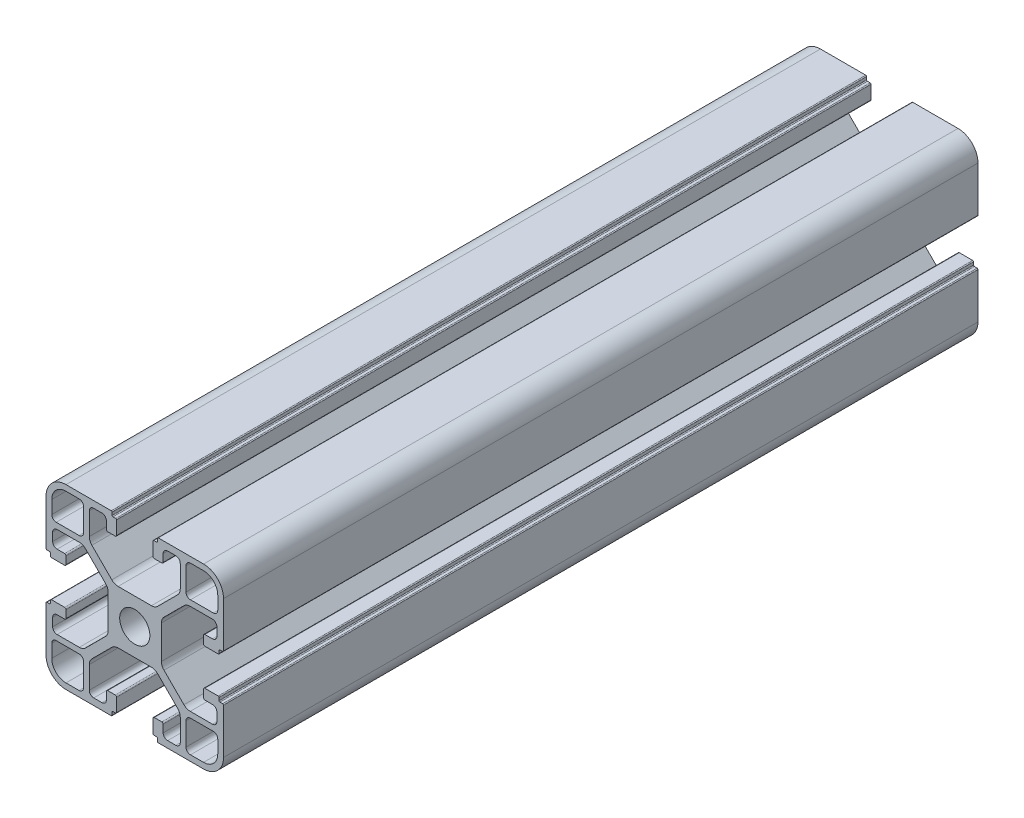
SolidWorks part; units mm, degrees
material "6063-T5"
ref_plane "Front Plane" through (0, 0, 0) normal (0, 0, 1) x (1, 0, 0)
ref_plane "Top Plane" through (0, 0, 0) normal (0, 1, 0) x (1, 0, 0)
ref_plane "Right Plane" through (0, 0, 0) normal (1, 0, 0) x (0, 0, -1)
sketch "Sketch2" plane through (0, 0, 0) normal (0, 0, 1) x (1, 0, 0)
  line L0 (4.5, 0) -> (14.7, 0)
  line L1 (40, 4.5) -> (40, 14.7)
  line L2 (35.5, 40) -> (25.3, 40)
  line L3 (0, 35.5) -> (0, 25.3)
  line L4 (15.9, 1.2) -> (15.9, 4.2)
  line L5 (24.1, 1.2) -> (24.1, 4.2)
  line L6 (38.8, 24.1) -> (35.8, 24.1)
  line L7 (35.5, 24.4) -> (35.5, 26.1)
  line L8 (14, 23.7574) -> (14, 16.2426)
  line L9 (16.2426, 14) -> (23.7574, 14)
  line L10 (26, 16.2426) -> (26, 23.7574)
  line L11 (13.4142, 14.8284) -> (8.9216, 10.3358)
  line L12 (23.7574, 26) -> (16.2426, 26)
  line L13 (4.5, 24.4) -> (4.5, 26.1)
  line L14 (1.2, 24.1) -> (4.2, 24.1)
  line L15 (15.9, 38.8) -> (15.9, 35.8)
  line L16 (14.8284, 26.5858) -> (10.3358, 31.0784)
  line L17 (13.4142, 25.1716) -> (8.9216, 29.6642)
  line L18 (14.8284, 13.4142) -> (10.3358, 8.9216)
  line L19 (25.1716, 13.4142) -> (29.6642, 8.9216)
  line L20 (26.5858, 14.8284) -> (31.0784, 10.3358)
  line L21 (26.5858, 25.1716) -> (31.0784, 29.6642)
  line L22 (25.1716, 26.5858) -> (29.6642, 31.0784)
  line L23 (24.1, 38.8) -> (24.1, 35.8)
  line L24 (14.7, 40) -> (4.5, 40)
  line L25 (25.3, 0) -> (35.5, 0)
  line L26 (38.8, 15.9) -> (35.8, 15.9)
  line L27 (40, 25.3) -> (40, 35.5)
  line L28 (1.2, 15.9) -> (4.2, 15.9)
  line L29 (0, 14.7) -> (0, 4.5)
  line L30 (4.5, 15.6) -> (4.5, 13.9)
  line L31 (35.5, 15.6) -> (35.5, 13.9)
  line L32 (15.6, 35.5) -> (13.9, 35.5)
  line L33 (24.4, 35.5) -> (26.1, 35.5)
  line L34 (15.6, 4.5) -> (13.9, 4.5)
  line L35 (24.4, 4.5) -> (26.1, 4.5)
  line L36 (12.6, 38.5) -> (10.75, 38.5)
  line L37 (1.5, 12.6) -> (1.5, 10.75)
  line L38 (27.4, 1.5) -> (29.25, 1.5)
  line L39 (38.5, 27.4) -> (38.5, 29.25)
  line L40 (38.5, 10.75) -> (38.5, 12.6)
  line L41 (29.25, 38.5) -> (27.4, 38.5)
  line L42 (1.5, 29.25) -> (1.5, 27.4)
  line L43 (10.75, 1.5) -> (12.6, 1.5)
  line L44 (35.8, 26.4) -> (37.5, 26.4)
  line L45 (35.8, 13.6) -> (37.5, 13.6)
  line L46 (4.2, 26.4) -> (2.5, 26.4)
  line L47 (13.6, 35.8) -> (13.6, 37.5)
  line L48 (26.4, 35.8) -> (26.4, 37.5)
  line L49 (4.2, 13.6) -> (2.5, 13.6)
  line L50 (13.6, 4.2) -> (13.6, 2.5)
  line L51 (26.4, 4.2) -> (26.4, 2.5)
  line L52 (9.75, 7.5074) -> (9.75, 2.5)
  line L53 (30.25, 7.5074) -> (30.25, 2.5)
  line L54 (9.75, 37.5) -> (9.75, 32.4926)
  line L55 (30.25, 37.5) -> (30.25, 32.4926)
  line L56 (32.4926, 30.25) -> (37.5, 30.25)
  line L57 (37.5, 9.75) -> (32.4926, 9.75)
  line L58 (2.5, 30.25) -> (7.5074, 30.25)
  line L59 (2.5, 9.75) -> (7.5074, 9.75)
  line L60 (31.55, 37.7) -> (31.55, 32.55)
  line L61 (32.55, 31.55) -> (37.7, 31.55)
  line L62 (1.3, 35.5) -> (1.3, 32.55)
  line L63 (4.5, 38.7) -> (7.45, 38.7)
  line L64 (32.55, 38.7) -> (35.5, 38.7)
  line L65 (38.7, 35.5) -> (38.7, 32.55)
  line L66 (8.45, 37.7) -> (8.45, 32.55)
  line L67 (2.3, 31.55) -> (7.45, 31.55)
  line L68 (1.3, 7.45) -> (1.3, 4.5)
  line L69 (2.3, 8.45) -> (7.45, 8.45)
  line L70 (8.45, 7.45) -> (8.45, 2.3)
  line L71 (4.5, 1.3) -> (7.45, 1.3)
  line L72 (31.55, 7.45) -> (31.55, 2.3)
  line L73 (32.55, 8.45) -> (37.7, 8.45)
  line L74 (38.7, 7.45) -> (38.7, 4.5)
  line L75 (32.55, 1.3) -> (35.5, 1.3)
  line L77 (14.9, 39.8) -> (14.9, 39.2)
  line L78 (15.1, 39) -> (15.7, 39)
  line L79 (25.1, 39.8) -> (25.1, 39.2)
  line L80 (24.9, 39) -> (24.3, 39)
  line L81 (25.1, 0.2) -> (25.1, 0.8)
  line L82 (24.9, 1) -> (24.3, 1)
  line L83 (14.9, 0.2) -> (14.9, 0.8)
  line L84 (15.1, 1) -> (15.7, 1)
  line L85 (0.2, 25.1) -> (0.8, 25.1)
  line L86 (1, 24.9) -> (1, 24.3)
  line L87 (0.2, 14.9) -> (0.8, 14.9)
  line L88 (1, 15.1) -> (1, 15.7)
  line L89 (39.8, 25.1) -> (39.2, 25.1)
  line L90 (39, 24.9) -> (39, 24.3)
  line L91 (39, 15.7) -> (39, 15.1)
  line L92 (39.2, 14.9) -> (39.8, 14.9)
  circle A0 centre (20, 20) radius 3.4
  arc A1 (1.3, 35.5) -> (4.5, 38.7) centre (4.5, 35.5) cw
  arc A2 (1.3, 4.5) -> (4.5, 1.3) centre (4.5, 4.5) ccw
  arc A3 (38.7, 4.5) -> (35.5, 1.3) centre (35.5, 4.5) cw
  arc A4 (35.5, 38.7) -> (38.7, 35.5) centre (35.5, 35.5) cw
  arc A5 (40, 35.5) -> (35.5, 40) centre (35.5, 35.5) ccw
  arc A6 (35.5, 0) -> (40, 4.5) centre (35.5, 4.5) ccw
  arc A7 (4.5, 0) -> (0, 4.5) centre (4.5, 4.5) cw
  arc A8 (4.5, 40) -> (0, 35.5) centre (4.5, 35.5) ccw
  arc A9 (13.4142, 14.8284) -> (14, 16.2426) centre (12, 16.2426) ccw
  arc A10 (7.5074, 9.75) -> (8.9216, 10.3358) centre (7.5074, 11.75) ccw
  arc A11 (9.75, 7.5074) -> (10.3358, 8.9216) centre (11.75, 7.5074) cw
  arc A12 (30.25, 7.5074) -> (29.6642, 8.9216) centre (28.25, 7.5074) ccw
  arc A13 (14.8284, 13.4142) -> (16.2426, 14) centre (16.2426, 12) cw
  arc A14 (25.1716, 13.4142) -> (23.7574, 14) centre (23.7574, 12) ccw
  arc A15 (32.4926, 9.75) -> (31.0784, 10.3358) centre (32.4926, 11.75) cw
  arc A16 (26.5858, 14.8284) -> (26, 16.2426) centre (28, 16.2426) cw
  arc A17 (32.4926, 30.25) -> (31.0784, 29.6642) centre (32.4926, 28.25) ccw
  arc A18 (26.5858, 25.1716) -> (26, 23.7574) centre (28, 23.7574) ccw
  arc A19 (13.4142, 25.1716) -> (14, 23.7574) centre (12, 23.7574) cw
  arc A20 (7.5074, 30.25) -> (8.9216, 29.6642) centre (7.5074, 28.25) cw
  arc A21 (9.75, 32.4926) -> (10.3358, 31.0784) centre (11.75, 32.4926) ccw
  arc A22 (30.25, 32.4926) -> (29.6642, 31.0784) centre (28.25, 32.4926) cw
  arc A23 (25.1716, 26.5858) -> (23.7574, 26) centre (23.7574, 28) cw
  arc A24 (14.8284, 26.5858) -> (16.2426, 26) centre (16.2426, 28) ccw
  arc A25 (37.7, 8.45) -> (38.7, 7.45) centre (37.7, 7.45) cw
  arc A26 (31.55, 2.3) -> (32.55, 1.3) centre (32.55, 2.3) ccw
  arc A27 (31.55, 7.45) -> (32.55, 8.45) centre (32.55, 7.45) cw
  arc A28 (8.45, 2.3) -> (7.45, 1.3) centre (7.45, 2.3) cw
  arc A29 (1.3, 7.45) -> (2.3, 8.45) centre (2.3, 7.45) cw
  arc A30 (7.45, 8.45) -> (8.45, 7.45) centre (7.45, 7.45) cw
  arc A31 (38.7, 32.55) -> (37.7, 31.55) centre (37.7, 32.55) cw
  arc A32 (31.55, 32.55) -> (32.55, 31.55) centre (32.55, 32.55) ccw
  arc A33 (31.55, 37.7) -> (32.55, 38.7) centre (32.55, 37.7) cw
  arc A34 (7.45, 38.7) -> (8.45, 37.7) centre (7.45, 37.7) cw
  arc A35 (8.45, 32.55) -> (7.45, 31.55) centre (7.45, 32.55) cw
  arc A36 (1.3, 32.55) -> (2.3, 31.55) centre (2.3, 32.55) ccw
  arc A37 (30.25, 2.5) -> (29.25, 1.5) centre (29.25, 2.5) cw
  arc A38 (26.4, 2.5) -> (27.4, 1.5) centre (27.4, 2.5) ccw
  arc A39 (13.6, 2.5) -> (12.6, 1.5) centre (12.6, 2.5) cw
  arc A40 (9.75, 2.5) -> (10.75, 1.5) centre (10.75, 2.5) ccw
  arc A41 (26.4, 37.5) -> (27.4, 38.5) centre (27.4, 37.5) cw
  arc A42 (30.25, 37.5) -> (29.25, 38.5) centre (29.25, 37.5) ccw
  arc A43 (37.5, 26.4) -> (38.5, 27.4) centre (37.5, 27.4) ccw
  arc A44 (37.5, 30.25) -> (38.5, 29.25) centre (37.5, 29.25) cw
  arc A45 (37.5, 13.6) -> (38.5, 12.6) centre (37.5, 12.6) cw
  arc A46 (37.5, 9.75) -> (38.5, 10.75) centre (37.5, 10.75) ccw
  arc A47 (2.5, 9.75) -> (1.5, 10.75) centre (2.5, 10.75) cw
  arc A48 (2.5, 13.6) -> (1.5, 12.6) centre (2.5, 12.6) ccw
  arc A49 (2.5, 26.4) -> (1.5, 27.4) centre (2.5, 27.4) cw
  arc A50 (2.5, 30.25) -> (1.5, 29.25) centre (2.5, 29.25) ccw
  arc A51 (9.75, 37.5) -> (10.75, 38.5) centre (10.75, 37.5) cw
  arc A52 (13.6, 37.5) -> (12.6, 38.5) centre (12.6, 37.5) ccw
  arc A53 (26.1, 35.5) -> (26.4, 35.8) centre (26.1, 35.8) ccw
  arc A54 (24.1, 35.8) -> (24.4, 35.5) centre (24.4, 35.8) ccw
  arc A55 (15.9, 35.8) -> (15.6, 35.5) centre (15.6, 35.8) cw
  arc A56 (13.9, 35.5) -> (13.6, 35.8) centre (13.9, 35.8) cw
  arc A57 (13.9, 4.5) -> (13.6, 4.2) centre (13.9, 4.2) ccw
  arc A58 (15.9, 4.2) -> (15.6, 4.5) centre (15.6, 4.2) ccw
  arc A59 (24.1, 4.2) -> (24.4, 4.5) centre (24.4, 4.2) cw
  arc A60 (26.1, 4.5) -> (26.4, 4.2) centre (26.1, 4.2) cw
  arc A61 (35.5, 13.9) -> (35.8, 13.6) centre (35.8, 13.9) ccw
  arc A62 (35.8, 15.9) -> (35.5, 15.6) centre (35.8, 15.6) ccw
  arc A63 (35.8, 24.1) -> (35.5, 24.4) centre (35.8, 24.4) cw
  arc A64 (35.5, 26.1) -> (35.8, 26.4) centre (35.8, 26.1) cw
  arc A65 (4.5, 13.9) -> (4.2, 13.6) centre (4.2, 13.9) cw
  arc A66 (4.2, 15.9) -> (4.5, 15.6) centre (4.2, 15.6) cw
  arc A67 (4.2, 24.1) -> (4.5, 24.4) centre (4.2, 24.4) ccw
  arc A68 (4.5, 26.1) -> (4.2, 26.4) centre (4.2, 26.1) ccw
  arc A69 (25.3, 0) -> (25.1, 0.2) centre (25.3, 0.2) cw
  arc A70 (25.1, 0.8) -> (24.9, 1) centre (24.9, 0.8) ccw
  arc A71 (24.3, 1) -> (24.1, 1.2) centre (24.3, 1.2) cw
  arc A72 (14.7, 0) -> (14.9, 0.2) centre (14.7, 0.2) ccw
  arc A73 (14.9, 0.8) -> (15.1, 1) centre (15.1, 0.8) cw
  arc A74 (15.7, 1) -> (15.9, 1.2) centre (15.7, 1.2) ccw
  arc A75 (39.8, 14.9) -> (40, 14.7) centre (39.8, 14.7) cw
  arc A76 (39, 15.1) -> (39.2, 14.9) centre (39.2, 15.1) ccw
  arc A77 (38.8, 15.9) -> (39, 15.7) centre (38.8, 15.7) cw
  arc A78 (0, 25.3) -> (0.2, 25.1) centre (0.2, 25.3) ccw
  arc A79 (0.8, 25.1) -> (1, 24.9) centre (0.8, 24.9) cw
  arc A80 (1, 24.3) -> (1.2, 24.1) centre (1.2, 24.3) ccw
  arc A81 (0, 14.7) -> (0.2, 14.9) centre (0.2, 14.7) cw
  arc A82 (0.8, 14.9) -> (1, 15.1) centre (0.8, 15.1) ccw
  arc A83 (1, 15.7) -> (1.2, 15.9) centre (1.2, 15.7) cw
  arc A84 (39, 24.3) -> (38.8, 24.1) centre (38.8, 24.3) cw
  arc A85 (39.2, 25.1) -> (39, 24.9) centre (39.2, 24.9) ccw
  arc A86 (40, 25.3) -> (39.8, 25.1) centre (39.8, 25.3) cw
  arc A87 (24.3, 39) -> (24.1, 38.8) centre (24.3, 38.8) ccw
  arc A88 (25.1, 39.2) -> (24.9, 39) centre (24.9, 39.2) cw
  arc A89 (25.3, 40) -> (25.1, 39.8) centre (25.3, 39.8) ccw
  arc A90 (14.9, 39.2) -> (15.1, 39) centre (15.1, 39.2) ccw
  arc A91 (15.7, 39) -> (15.9, 38.8) centre (15.7, 38.8) cw
  arc A92 (14.7, 40) -> (14.9, 39.8) centre (14.7, 39.8) cw
  point P93 (0, 0)
extrude "Boss-Extrude1" add sketch "Sketch2" along normal blind 170
sketch "Sketch3" plane through (0, 0, 170) normal (0, 0, 1) x (1, 0, 0)
  line L76 (25.3, 0) -> (35.5, 0)
  line L77 (40, 4.5) -> (40, 14.7)
  line L78 (39.8, 14.9) -> (39.2, 14.9)
  line L79 (39, 15.1) -> (39, 15.7)
  line L80 (38.8, 15.9) -> (35.8, 15.9)
  line L81 (35.5, 15.6) -> (35.5, 13.9)
  line L82 (35.8, 13.6) -> (37.5, 13.6)
  line L83 (38.5, 12.6) -> (38.5, 10.75)
  line L84 (37.5, 9.75) -> (32.4926, 9.75)
  line L85 (31.0784, 10.3358) -> (26.5858, 14.8284)
  line L86 (26, 16.2426) -> (26, 23.7574)
  line L87 (26.5858, 25.1716) -> (31.0784, 29.6642)
  line L88 (32.4926, 30.25) -> (37.5, 30.25)
  line L89 (38.5, 29.25) -> (38.5, 27.4)
  line L90 (37.5, 26.4) -> (35.8, 26.4)
  line L91 (35.5, 26.1) -> (35.5, 24.4)
  line L92 (35.8, 24.1) -> (38.8, 24.1)
  line L93 (39, 24.3) -> (39, 24.9)
  line L94 (39.2, 25.1) -> (39.8, 25.1)
  line L95 (40, 25.3) -> (40, 35.5)
  line L96 (35.5, 40) -> (25.3, 40)
  line L97 (25.1, 39.8) -> (25.1, 39.2)
  line L98 (24.9, 39) -> (24.3, 39)
  line L99 (24.1, 38.8) -> (24.1, 35.8)
  line L100 (24.4, 35.5) -> (26.1, 35.5)
  line L101 (26.4, 35.8) -> (26.4, 37.5)
  line L102 (27.4, 38.5) -> (29.25, 38.5)
  line L103 (30.25, 37.5) -> (30.25, 32.4926)
  line L104 (29.6642, 31.0784) -> (25.1716, 26.5858)
  line L105 (23.7574, 26) -> (16.2426, 26)
  line L106 (14.8284, 26.5858) -> (10.3358, 31.0784)
  line L107 (9.75, 32.4926) -> (9.75, 37.5)
  line L108 (10.75, 38.5) -> (12.6, 38.5)
  line L109 (13.6, 37.5) -> (13.6, 35.8)
  line L110 (13.9, 35.5) -> (15.6, 35.5)
  line L111 (15.9, 35.8) -> (15.9, 38.8)
  line L112 (15.7, 39) -> (15.1, 39)
  line L113 (14.9, 39.2) -> (14.9, 39.8)
  line L114 (14.7, 40) -> (4.5, 40)
  line L115 (0, 35.5) -> (0, 25.3)
  line L116 (0.2, 25.1) -> (0.8, 25.1)
  line L117 (1, 24.9) -> (1, 24.3)
  line L118 (1.2, 24.1) -> (4.2, 24.1)
  line L119 (4.5, 24.4) -> (4.5, 26.1)
  line L120 (4.2, 26.4) -> (2.5, 26.4)
  line L121 (1.5, 27.4) -> (1.5, 29.25)
  line L122 (2.5, 30.25) -> (7.5074, 30.25)
  line L123 (8.9216, 29.6642) -> (13.4142, 25.1716)
  line L124 (14, 23.7574) -> (14, 16.2426)
  line L125 (13.4142, 14.8284) -> (8.9216, 10.3358)
  line L126 (7.5074, 9.75) -> (2.5, 9.75)
  line L127 (1.5, 10.75) -> (1.5, 12.6)
  line L128 (2.5, 13.6) -> (4.2, 13.6)
  line L129 (4.5, 13.9) -> (4.5, 15.6)
  line L130 (4.2, 15.9) -> (1.2, 15.9)
  line L131 (1, 15.7) -> (1, 15.1)
  line L132 (0.8, 14.9) -> (0.2, 14.9)
  line L133 (0, 14.7) -> (0, 4.5)
  line L134 (4.5, 0) -> (14.7, 0)
  line L135 (14.9, 0.2) -> (14.9, 0.8)
  line L136 (15.1, 1) -> (15.7, 1)
  line L137 (15.9, 1.2) -> (15.9, 4.2)
  line L138 (15.6, 4.5) -> (13.9, 4.5)
  line L139 (13.6, 4.2) -> (13.6, 2.5)
  line L140 (12.6, 1.5) -> (10.75, 1.5)
  line L141 (9.75, 2.5) -> (9.75, 7.5074)
  line L142 (10.3358, 8.9216) -> (14.8284, 13.4142)
  line L143 (16.2426, 14) -> (23.7574, 14)
  line L144 (25.1716, 13.4142) -> (29.6642, 8.9216)
  line L145 (30.25, 7.5074) -> (30.25, 2.5)
  line L146 (29.25, 1.5) -> (27.4, 1.5)
  line L147 (26.4, 2.5) -> (26.4, 4.2)
  line L148 (26.1, 4.5) -> (24.4, 4.5)
  line L149 (24.1, 4.2) -> (24.1, 1.2)
  line L150 (24.3, 1) -> (24.9, 1)
  line L151 (25.1, 0.8) -> (25.1, 0.2)
  line L152 (25.3, 0) -> (35.5, 0)
  line L153 (40, 4.5) -> (40, 14.7)
  line L154 (39.8, 14.9) -> (39.2, 14.9)
  line L155 (39, 15.1) -> (39, 15.7)
  line L156 (38.8, 15.9) -> (35.8, 15.9)
  line L157 (35.5, 15.6) -> (35.5, 13.9)
  line L158 (35.8, 13.6) -> (37.5, 13.6)
  line L159 (38.5, 12.6) -> (38.5, 10.75)
  line L160 (37.5, 9.75) -> (32.4926, 9.75)
  line L161 (31.0784, 10.3358) -> (26.5858, 14.8284)
  line L162 (26, 16.2426) -> (26, 23.7574)
  line L163 (26.5858, 25.1716) -> (31.0784, 29.6642)
  line L164 (32.4926, 30.25) -> (37.5, 30.25)
  line L165 (38.5, 29.25) -> (38.5, 27.4)
  line L166 (37.5, 26.4) -> (35.8, 26.4)
  line L167 (35.5, 26.1) -> (35.5, 24.4)
  line L168 (35.8, 24.1) -> (38.8, 24.1)
  line L169 (39, 24.3) -> (39, 24.9)
  line L170 (39.2, 25.1) -> (39.8, 25.1)
  line L171 (40, 25.3) -> (40, 35.5)
  line L172 (35.5, 40) -> (25.3, 40)
  line L173 (25.1, 39.8) -> (25.1, 39.2)
  line L174 (24.9, 39) -> (24.3, 39)
  line L175 (24.1, 38.8) -> (24.1, 35.8)
  line L176 (24.4, 35.5) -> (26.1, 35.5)
  line L177 (26.4, 35.8) -> (26.4, 37.5)
  line L178 (27.4, 38.5) -> (29.25, 38.5)
  line L179 (30.25, 37.5) -> (30.25, 32.4926)
  line L180 (29.6642, 31.0784) -> (25.1716, 26.5858)
  line L181 (23.7574, 26) -> (16.2426, 26)
  line L182 (14.8284, 26.5858) -> (10.3358, 31.0784)
  line L183 (9.75, 32.4926) -> (9.75, 37.5)
  line L184 (10.75, 38.5) -> (12.6, 38.5)
  line L185 (13.6, 37.5) -> (13.6, 35.8)
  line L186 (13.9, 35.5) -> (15.6, 35.5)
  line L187 (15.9, 35.8) -> (15.9, 38.8)
  line L188 (15.7, 39) -> (15.1, 39)
  line L189 (14.9, 39.2) -> (14.9, 39.8)
  line L190 (14.7, 40) -> (4.5, 40)
  line L191 (0, 35.5) -> (0, 25.3)
  line L192 (0.2, 25.1) -> (0.8, 25.1)
  line L193 (1, 24.9) -> (1, 24.3)
  line L194 (1.2, 24.1) -> (4.2, 24.1)
  line L195 (4.5, 24.4) -> (4.5, 26.1)
  line L196 (4.2, 26.4) -> (2.5, 26.4)
  line L197 (1.5, 27.4) -> (1.5, 29.25)
  line L198 (2.5, 30.25) -> (7.5074, 30.25)
  line L199 (8.9216, 29.6642) -> (13.4142, 25.1716)
  line L200 (14, 23.7574) -> (14, 16.2426)
  line L201 (13.4142, 14.8284) -> (8.9216, 10.3358)
  line L202 (7.5074, 9.75) -> (2.5, 9.75)
  line L203 (1.5, 10.75) -> (1.5, 12.6)
  line L204 (2.5, 13.6) -> (4.2, 13.6)
  line L205 (4.5, 13.9) -> (4.5, 15.6)
  line L206 (4.2, 15.9) -> (1.2, 15.9)
  line L207 (1, 15.7) -> (1, 15.1)
  line L208 (0.8, 14.9) -> (0.2, 14.9)
  line L209 (0, 14.7) -> (0, 4.5)
  line L210 (4.5, 0) -> (14.7, 0)
  line L211 (14.9, 0.2) -> (14.9, 0.8)
  line L212 (15.1, 1) -> (15.7, 1)
  line L213 (15.9, 1.2) -> (15.9, 4.2)
  line L214 (15.6, 4.5) -> (13.9, 4.5)
  line L215 (13.6, 4.2) -> (13.6, 2.5)
  line L216 (12.6, 1.5) -> (10.75, 1.5)
  line L217 (9.75, 2.5) -> (9.75, 7.5074)
  line L218 (10.3358, 8.9216) -> (14.8284, 13.4142)
  line L219 (16.2426, 14) -> (23.7574, 14)
  line L220 (25.1716, 13.4142) -> (29.6642, 8.9216)
  line L221 (30.25, 7.5074) -> (30.25, 2.5)
  line L222 (29.25, 1.5) -> (27.4, 1.5)
  line L223 (26.4, 2.5) -> (26.4, 4.2)
  line L224 (26.1, 4.5) -> (24.4, 4.5)
  line L225 (24.1, 4.2) -> (24.1, 1.2)
  line L226 (24.3, 1) -> (24.9, 1)
  line L227 (25.1, 0.8) -> (25.1, 0.2)
  arc A76 (25.1, 0.2) -> (25.3, 0) centre (25.3, 0.2) ccw
  arc A77 (35.5, 0) -> (40, 4.5) centre (35.5, 4.5) ccw
  arc A78 (40, 14.7) -> (39.8, 14.9) centre (39.8, 14.7) ccw
  arc A79 (39, 15.1) -> (39.2, 14.9) centre (39.2, 15.1) ccw
  arc A80 (39, 15.7) -> (38.8, 15.9) centre (38.8, 15.7) ccw
  arc A81 (35.8, 15.9) -> (35.5, 15.6) centre (35.8, 15.6) ccw
  arc A82 (35.5, 13.9) -> (35.8, 13.6) centre (35.8, 13.9) ccw
  arc A83 (38.5, 12.6) -> (37.5, 13.6) centre (37.5, 12.6) ccw
  arc A84 (37.5, 9.75) -> (38.5, 10.75) centre (37.5, 10.75) ccw
  arc A85 (31.0784, 10.3358) -> (32.4926, 9.75) centre (32.4926, 11.75) ccw
  arc A86 (26, 16.2426) -> (26.5858, 14.8284) centre (28, 16.2426) ccw
  arc A87 (26.5858, 25.1716) -> (26, 23.7574) centre (28, 23.7574) ccw
  arc A88 (32.4926, 30.25) -> (31.0784, 29.6642) centre (32.4926, 28.25) ccw
  arc A89 (38.5, 29.25) -> (37.5, 30.25) centre (37.5, 29.25) ccw
  arc A90 (37.5, 26.4) -> (38.5, 27.4) centre (37.5, 27.4) ccw
  arc A91 (35.8, 26.4) -> (35.5, 26.1) centre (35.8, 26.1) ccw
  arc A92 (35.5, 24.4) -> (35.8, 24.1) centre (35.8, 24.4) ccw
  arc A93 (38.8, 24.1) -> (39, 24.3) centre (38.8, 24.3) ccw
  arc A94 (39.2, 25.1) -> (39, 24.9) centre (39.2, 24.9) ccw
  arc A95 (39.8, 25.1) -> (40, 25.3) centre (39.8, 25.3) ccw
  arc A96 (40, 35.5) -> (35.5, 40) centre (35.5, 35.5) ccw
  arc A97 (25.3, 40) -> (25.1, 39.8) centre (25.3, 39.8) ccw
  arc A98 (24.9, 39) -> (25.1, 39.2) centre (24.9, 39.2) ccw
  arc A99 (24.3, 39) -> (24.1, 38.8) centre (24.3, 38.8) ccw
  arc A100 (24.1, 35.8) -> (24.4, 35.5) centre (24.4, 35.8) ccw
  arc A101 (26.1, 35.5) -> (26.4, 35.8) centre (26.1, 35.8) ccw
  arc A102 (27.4, 38.5) -> (26.4, 37.5) centre (27.4, 37.5) ccw
  arc A103 (30.25, 37.5) -> (29.25, 38.5) centre (29.25, 37.5) ccw
  arc A104 (29.6642, 31.0784) -> (30.25, 32.4926) centre (28.25, 32.4926) ccw
  arc A105 (23.7574, 26) -> (25.1716, 26.5858) centre (23.7574, 28) ccw
  arc A106 (14.8284, 26.5858) -> (16.2426, 26) centre (16.2426, 28) ccw
  arc A107 (9.75, 32.4926) -> (10.3358, 31.0784) centre (11.75, 32.4926) ccw
  arc A108 (10.75, 38.5) -> (9.75, 37.5) centre (10.75, 37.5) ccw
  arc A109 (13.6, 37.5) -> (12.6, 38.5) centre (12.6, 37.5) ccw
  arc A110 (13.6, 35.8) -> (13.9, 35.5) centre (13.9, 35.8) ccw
  arc A111 (15.6, 35.5) -> (15.9, 35.8) centre (15.6, 35.8) ccw
  arc A112 (15.9, 38.8) -> (15.7, 39) centre (15.7, 38.8) ccw
  arc A113 (14.9, 39.2) -> (15.1, 39) centre (15.1, 39.2) ccw
  arc A114 (14.9, 39.8) -> (14.7, 40) centre (14.7, 39.8) ccw
  arc A115 (4.5, 40) -> (0, 35.5) centre (4.5, 35.5) ccw
  arc A116 (0, 25.3) -> (0.2, 25.1) centre (0.2, 25.3) ccw
  arc A117 (1, 24.9) -> (0.8, 25.1) centre (0.8, 24.9) ccw
  arc A118 (1, 24.3) -> (1.2, 24.1) centre (1.2, 24.3) ccw
  arc A119 (4.2, 24.1) -> (4.5, 24.4) centre (4.2, 24.4) ccw
  arc A120 (4.5, 26.1) -> (4.2, 26.4) centre (4.2, 26.1) ccw
  arc A121 (1.5, 27.4) -> (2.5, 26.4) centre (2.5, 27.4) ccw
  arc A122 (2.5, 30.25) -> (1.5, 29.25) centre (2.5, 29.25) ccw
  arc A123 (8.9216, 29.6642) -> (7.5074, 30.25) centre (7.5074, 28.25) ccw
  arc A124 (14, 23.7574) -> (13.4142, 25.1716) centre (12, 23.7574) ccw
  arc A125 (13.4142, 14.8284) -> (14, 16.2426) centre (12, 16.2426) ccw
  arc A126 (7.5074, 9.75) -> (8.9216, 10.3358) centre (7.5074, 11.75) ccw
  arc A127 (1.5, 10.75) -> (2.5, 9.75) centre (2.5, 10.75) ccw
  arc A128 (2.5, 13.6) -> (1.5, 12.6) centre (2.5, 12.6) ccw
  arc A129 (4.2, 13.6) -> (4.5, 13.9) centre (4.2, 13.9) ccw
  arc A130 (4.5, 15.6) -> (4.2, 15.9) centre (4.2, 15.6) ccw
  arc A131 (1.2, 15.9) -> (1, 15.7) centre (1.2, 15.7) ccw
  arc A132 (0.8, 14.9) -> (1, 15.1) centre (0.8, 15.1) ccw
  arc A133 (0.2, 14.9) -> (0, 14.7) centre (0.2, 14.7) ccw
  arc A134 (0, 4.5) -> (4.5, 0) centre (4.5, 4.5) ccw
  arc A135 (14.7, 0) -> (14.9, 0.2) centre (14.7, 0.2) ccw
  arc A136 (15.1, 1) -> (14.9, 0.8) centre (15.1, 0.8) ccw
  arc A137 (15.7, 1) -> (15.9, 1.2) centre (15.7, 1.2) ccw
  arc A138 (15.9, 4.2) -> (15.6, 4.5) centre (15.6, 4.2) ccw
  arc A139 (13.9, 4.5) -> (13.6, 4.2) centre (13.9, 4.2) ccw
  arc A140 (12.6, 1.5) -> (13.6, 2.5) centre (12.6, 2.5) ccw
  arc A141 (9.75, 2.5) -> (10.75, 1.5) centre (10.75, 2.5) ccw
  arc A142 (10.3358, 8.9216) -> (9.75, 7.5074) centre (11.75, 7.5074) ccw
  arc A143 (16.2426, 14) -> (14.8284, 13.4142) centre (16.2426, 12) ccw
  arc A144 (25.1716, 13.4142) -> (23.7574, 14) centre (23.7574, 12) ccw
  arc A145 (30.25, 7.5074) -> (29.6642, 8.9216) centre (28.25, 7.5074) ccw
  arc A146 (29.25, 1.5) -> (30.25, 2.5) centre (29.25, 2.5) ccw
  arc A147 (26.4, 2.5) -> (27.4, 1.5) centre (27.4, 2.5) ccw
  arc A148 (26.4, 4.2) -> (26.1, 4.5) centre (26.1, 4.2) ccw
  arc A149 (24.4, 4.5) -> (24.1, 4.2) centre (24.4, 4.2) ccw
  arc A150 (24.1, 1.2) -> (24.3, 1) centre (24.3, 1.2) ccw
  arc A151 (25.1, 0.8) -> (24.9, 1) centre (24.9, 0.8) ccw
  arc A152 (25.1, 0.2) -> (25.3, 0) centre (25.3, 0.2) ccw
  arc A153 (35.5, 0) -> (40, 4.5) centre (35.5, 4.5) ccw
  arc A154 (40, 14.7) -> (39.8, 14.9) centre (39.8, 14.7) ccw
  arc A155 (39, 15.1) -> (39.2, 14.9) centre (39.2, 15.1) ccw
  arc A156 (39, 15.7) -> (38.8, 15.9) centre (38.8, 15.7) ccw
  arc A157 (35.8, 15.9) -> (35.5, 15.6) centre (35.8, 15.6) ccw
  arc A158 (35.5, 13.9) -> (35.8, 13.6) centre (35.8, 13.9) ccw
  arc A159 (38.5, 12.6) -> (37.5, 13.6) centre (37.5, 12.6) ccw
  arc A160 (37.5, 9.75) -> (38.5, 10.75) centre (37.5, 10.75) ccw
  arc A161 (31.0784, 10.3358) -> (32.4926, 9.75) centre (32.4926, 11.75) ccw
  arc A162 (26, 16.2426) -> (26.5858, 14.8284) centre (28, 16.2426) ccw
  arc A163 (26.5858, 25.1716) -> (26, 23.7574) centre (28, 23.7574) ccw
  arc A164 (32.4926, 30.25) -> (31.0784, 29.6642) centre (32.4926, 28.25) ccw
  arc A165 (38.5, 29.25) -> (37.5, 30.25) centre (37.5, 29.25) ccw
  arc A166 (37.5, 26.4) -> (38.5, 27.4) centre (37.5, 27.4) ccw
  arc A167 (35.8, 26.4) -> (35.5, 26.1) centre (35.8, 26.1) ccw
  arc A168 (35.5, 24.4) -> (35.8, 24.1) centre (35.8, 24.4) ccw
  arc A169 (38.8, 24.1) -> (39, 24.3) centre (38.8, 24.3) ccw
  arc A170 (39.2, 25.1) -> (39, 24.9) centre (39.2, 24.9) ccw
  arc A171 (39.8, 25.1) -> (40, 25.3) centre (39.8, 25.3) ccw
  arc A172 (40, 35.5) -> (35.5, 40) centre (35.5, 35.5) ccw
  arc A173 (25.3, 40) -> (25.1, 39.8) centre (25.3, 39.8) ccw
  arc A174 (24.9, 39) -> (25.1, 39.2) centre (24.9, 39.2) ccw
  arc A175 (24.3, 39) -> (24.1, 38.8) centre (24.3, 38.8) ccw
  arc A176 (24.1, 35.8) -> (24.4, 35.5) centre (24.4, 35.8) ccw
  arc A177 (26.1, 35.5) -> (26.4, 35.8) centre (26.1, 35.8) ccw
  arc A178 (27.4, 38.5) -> (26.4, 37.5) centre (27.4, 37.5) ccw
  arc A179 (30.25, 37.5) -> (29.25, 38.5) centre (29.25, 37.5) ccw
  arc A180 (29.6642, 31.0784) -> (30.25, 32.4926) centre (28.25, 32.4926) ccw
  arc A181 (23.7574, 26) -> (25.1716, 26.5858) centre (23.7574, 28) ccw
  arc A182 (14.8284, 26.5858) -> (16.2426, 26) centre (16.2426, 28) ccw
  arc A183 (9.75, 32.4926) -> (10.3358, 31.0784) centre (11.75, 32.4926) ccw
  arc A184 (10.75, 38.5) -> (9.75, 37.5) centre (10.75, 37.5) ccw
  arc A185 (13.6, 37.5) -> (12.6, 38.5) centre (12.6, 37.5) ccw
  arc A186 (13.6, 35.8) -> (13.9, 35.5) centre (13.9, 35.8) ccw
  arc A187 (15.6, 35.5) -> (15.9, 35.8) centre (15.6, 35.8) ccw
  arc A188 (15.9, 38.8) -> (15.7, 39) centre (15.7, 38.8) ccw
  arc A189 (14.9, 39.2) -> (15.1, 39) centre (15.1, 39.2) ccw
  arc A190 (14.9, 39.8) -> (14.7, 40) centre (14.7, 39.8) ccw
  arc A191 (4.5, 40) -> (0, 35.5) centre (4.5, 35.5) ccw
  arc A192 (0, 25.3) -> (0.2, 25.1) centre (0.2, 25.3) ccw
  arc A193 (1, 24.9) -> (0.8, 25.1) centre (0.8, 24.9) ccw
  arc A194 (1, 24.3) -> (1.2, 24.1) centre (1.2, 24.3) ccw
  arc A195 (4.2, 24.1) -> (4.5, 24.4) centre (4.2, 24.4) ccw
  arc A196 (4.5, 26.1) -> (4.2, 26.4) centre (4.2, 26.1) ccw
  arc A197 (1.5, 27.4) -> (2.5, 26.4) centre (2.5, 27.4) ccw
  arc A198 (2.5, 30.25) -> (1.5, 29.25) centre (2.5, 29.25) ccw
  arc A199 (8.9216, 29.6642) -> (7.5074, 30.25) centre (7.5074, 28.25) ccw
  arc A200 (14, 23.7574) -> (13.4142, 25.1716) centre (12, 23.7574) ccw
  arc A201 (13.4142, 14.8284) -> (14, 16.2426) centre (12, 16.2426) ccw
  arc A202 (7.5074, 9.75) -> (8.9216, 10.3358) centre (7.5074, 11.75) ccw
  arc A203 (1.5, 10.75) -> (2.5, 9.75) centre (2.5, 10.75) ccw
  arc A204 (2.5, 13.6) -> (1.5, 12.6) centre (2.5, 12.6) ccw
  arc A205 (4.2, 13.6) -> (4.5, 13.9) centre (4.2, 13.9) ccw
  arc A206 (4.5, 15.6) -> (4.2, 15.9) centre (4.2, 15.6) ccw
  arc A207 (1.2, 15.9) -> (1, 15.7) centre (1.2, 15.7) ccw
  arc A208 (0.8, 14.9) -> (1, 15.1) centre (0.8, 15.1) ccw
  arc A209 (0.2, 14.9) -> (0, 14.7) centre (0.2, 14.7) ccw
  arc A210 (0, 4.5) -> (4.5, 0) centre (4.5, 4.5) ccw
  arc A211 (14.7, 0) -> (14.9, 0.2) centre (14.7, 0.2) ccw
  arc A212 (15.1, 1) -> (14.9, 0.8) centre (15.1, 0.8) ccw
  arc A213 (15.7, 1) -> (15.9, 1.2) centre (15.7, 1.2) ccw
  arc A214 (15.9, 4.2) -> (15.6, 4.5) centre (15.6, 4.2) ccw
  arc A215 (13.9, 4.5) -> (13.6, 4.2) centre (13.9, 4.2) ccw
  arc A216 (12.6, 1.5) -> (13.6, 2.5) centre (12.6, 2.5) ccw
  arc A217 (9.75, 2.5) -> (10.75, 1.5) centre (10.75, 2.5) ccw
  arc A218 (10.3358, 8.9216) -> (9.75, 7.5074) centre (11.75, 7.5074) ccw
  arc A219 (16.2426, 14) -> (14.8284, 13.4142) centre (16.2426, 12) ccw
  arc A220 (25.1716, 13.4142) -> (23.7574, 14) centre (23.7574, 12) ccw
  arc A221 (30.25, 7.5074) -> (29.6642, 8.9216) centre (28.25, 7.5074) ccw
  arc A222 (29.25, 1.5) -> (30.25, 2.5) centre (29.25, 2.5) ccw
  arc A223 (26.4, 2.5) -> (27.4, 1.5) centre (27.4, 2.5) ccw
  arc A224 (26.4, 4.2) -> (26.1, 4.5) centre (26.1, 4.2) ccw
  arc A225 (24.4, 4.5) -> (24.1, 4.2) centre (24.4, 4.2) ccw
  arc A226 (24.1, 1.2) -> (24.3, 1) centre (24.3, 1.2) ccw
  arc A227 (25.1, 0.8) -> (24.9, 1) centre (24.9, 0.8) ccw
  dimension "D1" = 0
